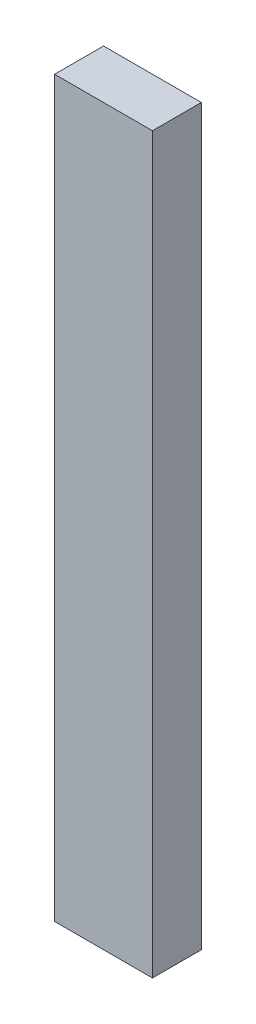
SolidWorks part; units mm, degrees
ref_plane "Plan de face" through (0, 0, 0) normal (0, 0, 1) x (1, 0, 0)
ref_plane "Plan de dessus" through (0, 0, 0) normal (0, 1, 0) x (1, 0, 0)
ref_plane "Plan de droite" through (0, 0, 0) normal (1, 0, 0) x (0, 0, -1)
sketch "Esquisse1" plane through (0, 0, 0) normal (0, 0, 1) x (1, 0, 0)
  line L0 (-38.3952, 38.2527) -> (-45.4952, 38.2527) construction
  line L1 (-45.4952, 38.2527) -> (-44.9452, 22.2527)
  line L2 (-38.3952, 38.2527) -> (-38.9452, 22.2527)
  line L4 (-51.9452, 48.2527) -> (-31.9452, 48.2527)
  line L5 (-51.9452, 48.2527) -> (-51.9452, -101.7473)
  line L6 (-51.9452, -101.7473) -> (-31.9452, -101.7473)
  line L7 (-31.9452, 48.2527) -> (-31.9452, -101.7473)
  arc A0 (-38.3952, 38.2527) -> (-45.4952, 38.2527) centre (-41.9452, 38.2527) ccw
  arc A1 (-44.9452, 22.2527) -> (-38.9452, 22.2527) centre (-41.9452, 22.2527) ccw
  dimension "D1" = 7.1
  dimension "D3" = 3
  dimension "D4" = 10
  dimension "D5" = 10
  dimension "D6" = 10
  dimension "D2" = 16
  dimension "D7" = 150
extrude "Boss.-Extru.1" add sketch "Esquisse1" along normal blind 5
sketch "Esquisse2" plane through (0, 0, 5) normal (0, 0, 1) x (1, 0, 0)
  line L1 (-51.9452, 48.2527) -> (-31.9452, 48.2527)
  line L2 (-51.9452, 48.2527) -> (-51.9452, -101.7473)
  line L3 (-51.9452, -101.7473) -> (-31.9452, -101.7473)
  line L4 (-31.9452, 48.2527) -> (-31.9452, -101.7473)
extrude "Boss.-Extru.2" add sketch "Esquisse2" along normal blind 5
